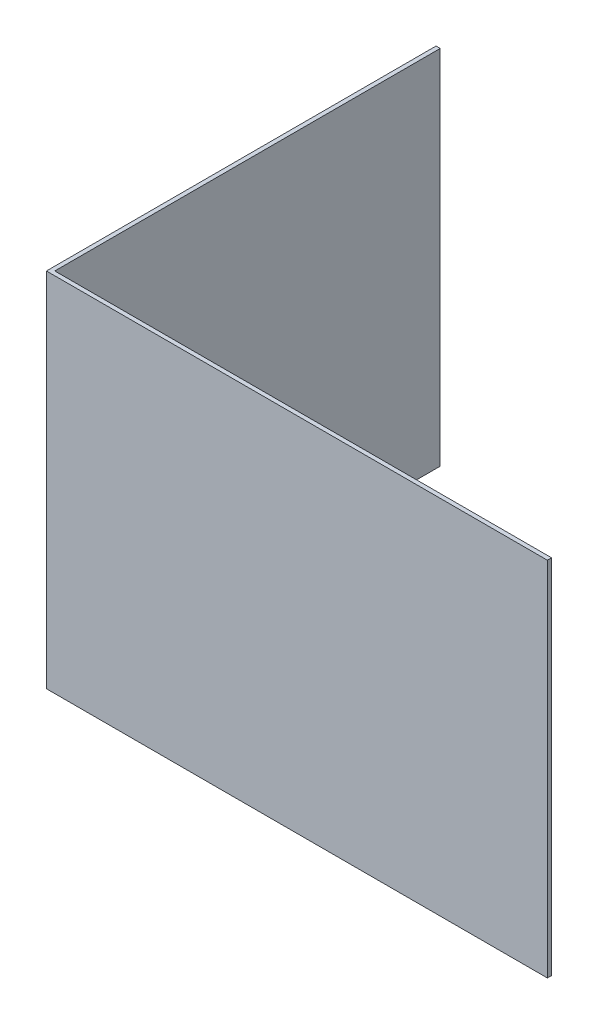
SolidWorks part; units mm, degrees
ref_plane "Front Plane" through (0, 0, 0) normal (0, 0, 1) x (1, 0, 0)
ref_plane "Top Plane" through (0, 0, 0) normal (0, 1, 0) x (1, 0, 0)
ref_plane "Right Plane" through (0, 0, 0) normal (1, 0, 0) x (0, 0, -1)
sketch "Sketch3" plane through (0, 0, 0) normal (0, 1, 0) x (1, 0, 0)
  line L0 (-49.266, 15.4658) -> (-49.266, -124.5342)
  line L1 (-49.266, -124.5342) -> (130.734, -124.5342)
  line L2 (130.734, -124.5342) -> (130.734, -123.0342)
  line L3 (130.734, -123.0342) -> (-47.766, -123.0342)
  line L4 (-47.766, -123.0342) -> (-47.766, 15.4658)
  line L5 (-47.766, 15.4658) -> (-49.266, 15.4658)
  dimension "D1" = 1.5
  dimension "D2" = 1.5
  dimension "D3" = 180
  dimension "D4" = 140
extrude "Boss-Extrude2" add sketch "Sketch3" along normal blind 130
